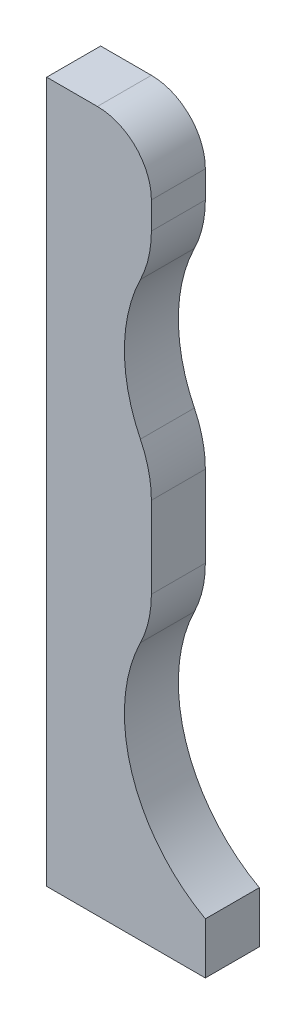
SolidWorks part; units mm, degrees
ref_plane "Front Plane" through (0, 0, 0) normal (0, 0, 1) x (1, 0, 0)
ref_plane "Top Plane" through (0, 0, 0) normal (0, 1, 0) x (1, 0, 0)
ref_plane "Right Plane" through (0, 0, 0) normal (1, 0, 0) x (0, 0, -1)
sketch "Sketch1" plane through (0, 0, 0) normal (0, 0, 1) x (1, 0, 0)
  line L0 (3197.6441, 2688.5637) -> (3197.6441, 2647.3354)
  line L1 (3197.6441, 2688.5637) -> (3200.6286, 2688.5637)
  line L2 (3197.6441, 2647.3354) -> (3206.9786, 2647.3354)
  line L3 (3206.9786, 2647.3354) -> (3206.9786, 2650.3493)
  line L4 (3203.8036, 2665.2959) -> (3203.8036, 2670.0861)
  line L5 (3203.8036, 2683.7998) -> (3203.8036, 2685.3887)
  arc A0 (3203.1575, 2662.5051) -> (3206.9786, 2650.3493) centre (3211.4681, 2658.439) ccw
  arc A1 (3203.1575, 2662.5051) -> (3203.8036, 2665.2959) centre (3197.4536, 2665.2959) ccw
  arc A2 (3203.1575, 2681.009) -> (3203.1575, 2672.8768) centre (3211.4681, 2676.9429) ccw
  arc A3 (3203.1575, 2681.009) -> (3203.8036, 2683.7998) centre (3197.4536, 2683.7998) ccw
  arc A4 (3203.8036, 2670.0861) -> (3203.1575, 2672.8768) centre (3197.4536, 2670.0861) ccw
  arc A5 (3203.8036, 2685.3887) -> (3200.6286, 2688.5637) centre (3200.6286, 2685.3887) ccw
extrude "Boss-Extrude1" add sketch "Sketch1" along normal blind 3.175
